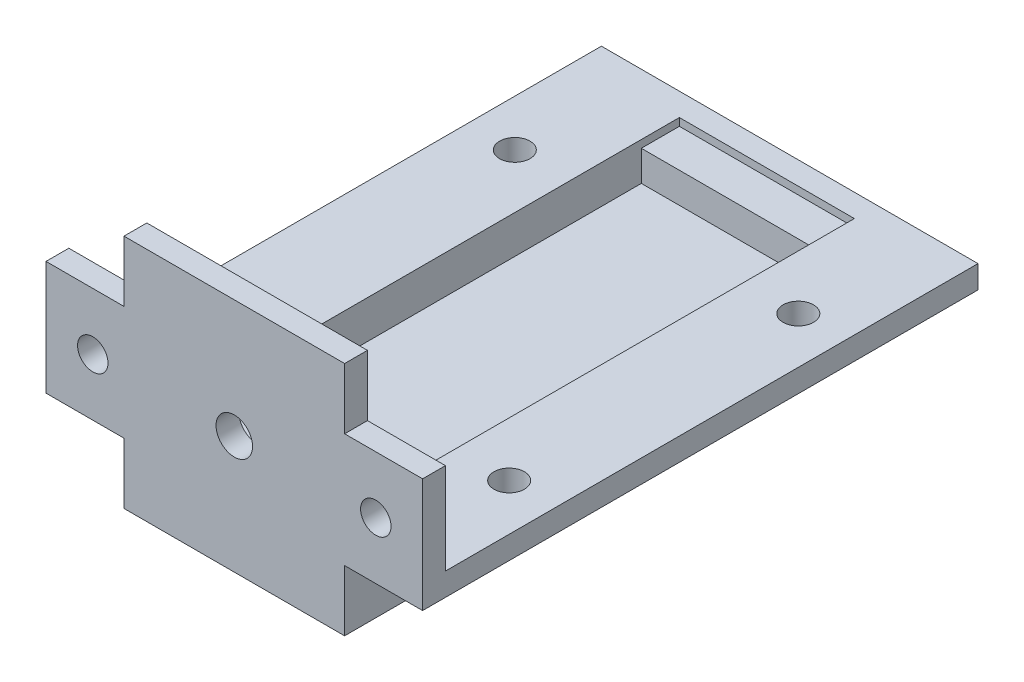
SolidWorks part; units mm, degrees
ref_plane "Alzado" through (0, 0, 0) normal (0, 0, 1) x (1, 0, 0)
ref_plane "Planta" through (0, 0, 0) normal (0, 1, 0) x (1, 0, 0)
ref_plane "Vista lateral" through (0, 0, 0) normal (1, 0, 0) x (0, 0, -1)
sketch "Croquis4" plane through (0, 0, 0) normal (0, 0, 1) x (1, 0, 0)
  line L1 (14.5, 16) -> (-14.5, 16)
  line L2 (-14.5, 16) -> (-14.5, 8)
  line L3 (-14.5, 8) -> (-24.75, 8)
  line L4 (-24.75, 8) -> (-24.75, -7)
  line L5 (-24.75, -7) -> (-14.5, -7)
  line L6 (-14.5, -7) -> (-14.5, -15)
  line L7 (-14.5, -15) -> (14.5, -15)
  line L8 (14.5, -7) -> (14.5, -15)
  line L9 (24.75, -7) -> (14.5, -7)
  line L10 (24.75, 8) -> (24.75, -7)
  line L11 (14.5, 8) -> (24.75, 8)
  line L12 (14.5, 16) -> (14.5, 8)
  point P4 (0, 0)
  dimension "D1" = 29
  dimension "D2" = 10.25
  dimension "D3" = 8
  dimension "D4" = 15
extrude "Saliente-Extruir2" add sketch "Croquis4" along normal blind 3
sketch "Croquis5" plane through (0, 0, 0) normal (0, 0, -1) x (-1, 0, 0)
  line L26 (-24.75, -4) -> (-24.75, -7)
  line L27 (-24.75, -7) -> (-24.75, 8) construction
  line L28 (-24.75, -7) -> (-14.5, -7)
  line L29 (14.5, -7) -> (24.75, -7)
  line L31 (24.75, -7) -> (24.75, -4)
  line L32 (-14.5, -7) -> (-24.75, -7) construction
  line L33 (24.75, 8) -> (24.75, -7) construction
  line L34 (24.75, -4) -> (-24.75, -4)
  line L38 (-14.5, -7) -> (-14.5, -15)
  line L39 (-14.5, -15) -> (14.5, -15)
  line L40 (14.5, -7) -> (14.5, -15) construction
  line L41 (14.5, -15) -> (14.5, -7)
  dimension "D1" = 3
extrude "Saliente-Extruir3" add sketch "Croquis5" along normal blind 70
sketch "croquis hueco motor" plane through (0, -4, 0) normal (0, 1, 0) x (1, 0, 0)
  line L0 (14.5, 0) -> (-14.5, 0) construction
  line L6 (-11.5, 0) -> (11.5, 0)
  line L8 (-11.5, 0) -> (-11.5, 67)
  line L12 (-11.5, 67) -> (11.5, 67)
  line L14 (11.5, 0) -> (11.5, 67)
  line L17 (-24.75, 70) -> (24.75, 70) construction
  line L18 (-11.5, 54.716) -> (-24.75, 54.716) construction
  line L19 (-24.75, 70) -> (-24.75, 0) construction
  line L20 (11.5, 55.3959) -> (24.75, 55.3959) construction
  line L21 (24.75, 70) -> (24.75, 0) construction
  dimension "D1" = 23
  dimension "D2" = 3
extrude "hueco motor" cut sketch "croquis hueco motor" against normal blind 5
sketch "Croquis10" plane through (0, 0, 3) normal (0, 0, 1) x (1, 0, 0)
  line L0 (-14.5, 16) -> (14.5, -15) construction
  line L1 (14.5, -15) -> (14.5, 16) construction
  line L2 (14.5, 16) -> (-14.5, -15) construction
  line L3 (-24.75, 8) -> (-24.75, -7) construction
  line L5 (-14.5, 8) -> (-24.75, 8) construction
  line L6 (0, 0.5) -> (0, 16) construction
  line L9 (14.5, 16) -> (-14.5, 16) construction
  circle A0 centre (0, 0.5) radius 2.4
  circle A1 centre (-18.6, 0.5) radius 2
  circle A2 centre (18.6, 0.5) radius 2
  dimension "D1" = 6.15
  dimension "D2" = 4
  dimension "D3" = 7.5
extrude "tornillo y motor" cut sketch "Croquis10" against normal blind 5
sketch "Croquis12" plane through (0, -9, 0) normal (0, 1, 0) x (1, 0, 0)
  line L6 (11.5, 0) -> (11.5, 67) construction
  line L7 (-11.5, 67) -> (11.5, 67)
  line L8 (-11.5, 67) -> (-11.5, 62)
  line L9 (-11.5, 62) -> (11.5, 62)
  line L10 (11.5, 67) -> (11.5, 62)
  dimension "D1" = 5
extrude "Saliente-Extruir5" add sketch "Croquis12" along normal blind 4
sketch "Croquis16" plane through (0, -4, 0) normal (0, 1, 0) x (1, 0, 0)
  line L0 (-18.63, 52.5) -> (18.63, 52.5) construction
  line L1 (18.63, 52.5) -> (18.63, 14.5) construction
  line L2 (-18.63, 52.5) -> (-24.75, 52.5) construction
  line L3 (24.75, 70) -> (24.75, 0) construction
  line L7 (-18.63, 14.5) -> (-24.7537, 14.5) construction
  line L10 (18.63, 14.5) -> (24.7537, 14.5) construction
  line L12 (18.63, 52.5) -> (24.7446, 52.1673) construction
  line L13 (-24.75, 70) -> (-24.75, 0) construction
  circle A0 centre (-18.63, 52.5) radius 2
  circle A1 centre (-18.63, 14.5) radius 2
  circle A2 centre (18.63, 14.5) radius 2
  circle A3 centre (18.63, 52.5) radius 2
  dimension "D1" = 38
  dimension "D2" = 38
  dimension "D3" = 6.12
  dimension "D4" = 6.12
extrude "Cortar-Extruir4" cut sketch "Croquis16" against normal through all
